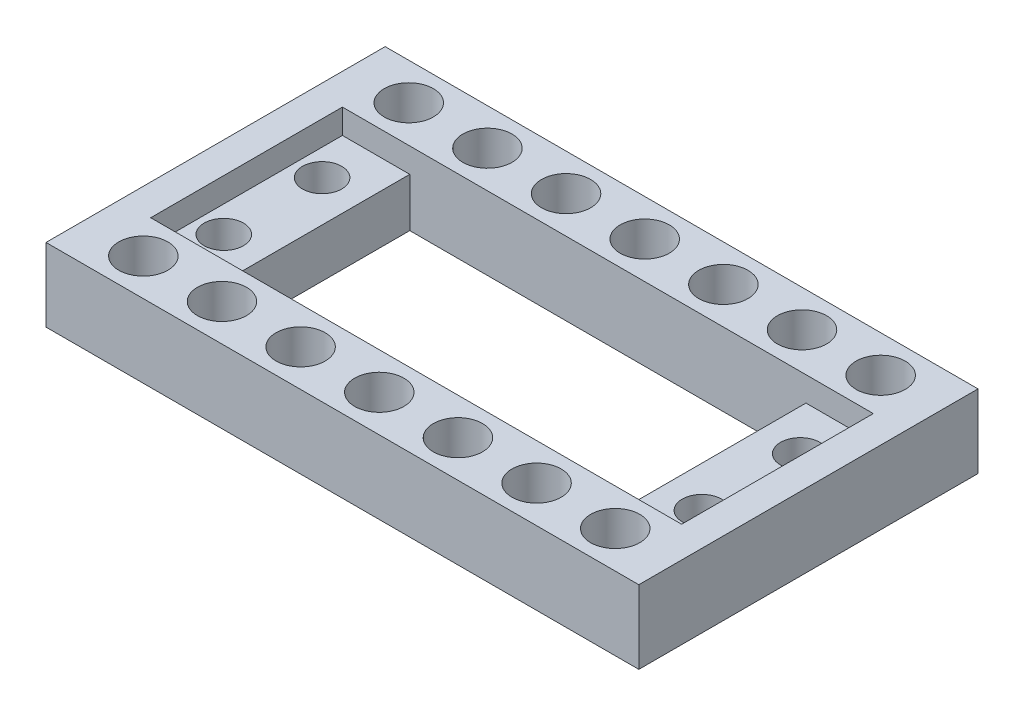
SolidWorks part; units mm, degrees
ref_plane "Front Plane" through (0, 0, 0) normal (0, 0, 1) x (1, 0, 0)
ref_plane "Top Plane" through (0, 0, 0) normal (0, 1, 0) x (1, 0, 0)
ref_plane "Right Plane" through (0, 0, 0) normal (1, 0, 0) x (0, 0, -1)
sketch "Sketch1" plane through (0, 0, 0) normal (0, 1, 0) x (1, 0, 0)
  line L0 (-34.3973, 0) -> (32.9918, 0) construction
  line L1 (-20.15, 9.75) -> (20.15, 9.75)
  line L2 (-20.15, 9.75) -> (-20.15, -9.75)
  line L3 (-20.15, -9.75) -> (20.15, -9.75)
  line L4 (20.15, 9.75) -> (20.15, -9.75)
  line L5 (-20.15, 9.75) -> (20.15, -9.75) construction
  line L6 (-20.15, -9.75) -> (20.15, 9.75) construction
  line L7 (0, 26.5192) -> (0, -28.2205) construction
  line L9 (-30.15, 17.25) -> (30.15, 17.25)
  line L10 (-30.15, 17.25) -> (-30.15, -17.25)
  line L11 (-30.15, -17.25) -> (30.15, -17.25)
  line L12 (30.15, 17.25) -> (30.15, -17.25)
  line L13 (-27, 9.75) -> (27, 9.75) construction
  line L14 (-27, 9.75) -> (-27, -9.75) construction
  line L15 (-27, -9.75) -> (27, -9.75) construction
  line L16 (27, 9.75) -> (27, -9.75) construction
  line L17 (-27, 9.75) -> (27, -9.75) construction
  line L18 (-27, -9.75) -> (27, 9.75) construction
  circle A0 centre (-24.315, -5) radius 2
  circle A1 centre (-24.315, 5) radius 2
  circle A2 centre (24.315, -5) radius 2
  circle A3 centre (24.315, 5) radius 2
  point P0 (0, 0)
  point P14 (0, 0)
  dimension "D9" = 24.315
  dimension "D8" = 4
  dimension "D10" = 5
  dimension "D1" = 40.3
  dimension "D2" = 19.5
  dimension "D3" = 7.5
  dimension "D4" = 7.5
  dimension "D5" = 10
  dimension "D6" = 10
  dimension "D7" = 54
extrude "Boss-Extrude1" add sketch "Sketch1" along normal blind 7.46
sketch "Sketch3" plane through (0, 7.46, 0) normal (0, 1, 0) x (1, 0, 0)
  line L1 (-27, 9.75) -> (27, 9.75)
  line L2 (-27, 9.75) -> (-27, -9.75)
  line L3 (-27, -9.75) -> (27, -9.75)
  line L4 (27, 9.75) -> (27, -9.75)
  line L5 (-27, 9.75) -> (27, -9.75) construction
  line L6 (-27, -9.75) -> (27, 9.75) construction
  point P0 (0, 0)
  dimension "D1" = 19.5
  dimension "D2" = 54
extrude "Cut-Extrude1" cut sketch "Sketch3" against normal blind 2.5
sketch "Sketch4" plane through (0, 7.46, 0) normal (0, 1, 0) x (1, 0, 0)
  line L0 (0, 17.25) -> (0, 9.75) construction
  line L1 (30.15, 17.25) -> (-30.15, 17.25) construction
  line L2 (27, 9.75) -> (-27, 9.75) construction
  line L3 (0, 13.5) -> (-30.15, 13.5) construction
  line L4 (-30.15, 17.25) -> (-30.15, -17.25) construction
  line L5 (-20.15, 0) -> (20.15, 0) construction
  line L6 (-20.15, 9.75) -> (-20.15, -9.75) construction
  line L7 (20.15, -9.75) -> (20.15, 9.75) construction
  circle A0 centre (0, 13.5) radius 2.5
  circle A1 centre (8, 13.5) radius 2.5
  circle A2 centre (16, 13.5) radius 2.5
  circle A3 centre (24, 13.5) radius 2.5
  circle A4 centre (-24, 13.5) radius 2.5
  circle A5 centre (-16, 13.5) radius 2.5
  circle A6 centre (-8, 13.5) radius 2.5
  circle A7 centre (24, -13.5) radius 2.5
  circle A8 centre (16, -13.5) radius 2.5
  circle A9 centre (8, -13.5) radius 2.5
  circle A10 centre (0, -13.5) radius 2.5
  circle A11 centre (-8, -13.5) radius 2.5
  circle A12 centre (-16, -13.5) radius 2.5
  circle A13 centre (-24, -13.5) radius 2.5
  dimension "D1" = 5
  dimension "D3" = 8
  dimension "D2" = 4
extrude "Cut-Extrude2" cut sketch "Sketch4" against normal through all
